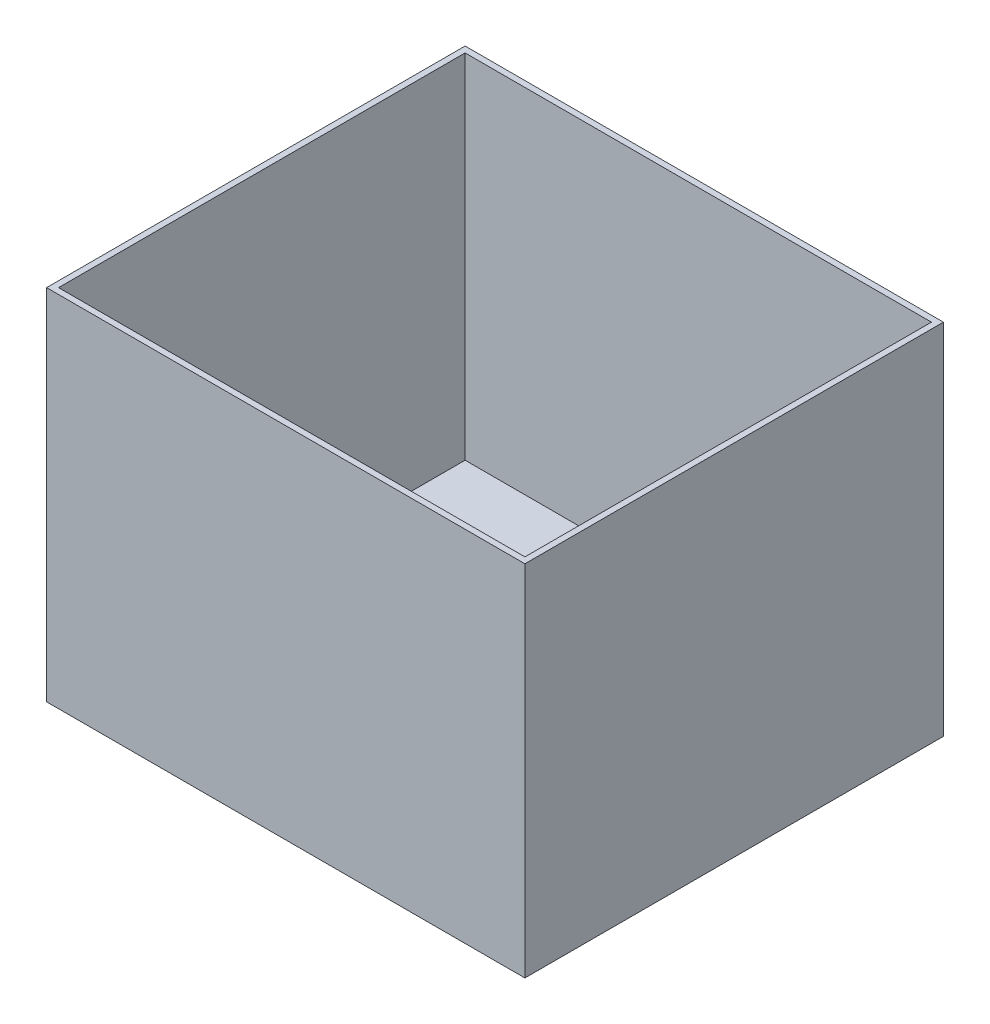
SolidWorks part; units mm, degrees
ref_plane "Front Plane" through (0, 0, 0) normal (0, 0, 1) x (1, 0, 0)
ref_plane "Top Plane" through (0, 0, 0) normal (0, 1, 0) x (1, 0, 0)
ref_plane "Right Plane" through (0, 0, 0) normal (1, 0, 0) x (0, 0, -1)
sketch "Sketch1" plane through (0, 0, 0) normal (0, 1, 0) x (1, 0, 0)
  line L1 (0, 0) -> (400, 0)
  line L2 (0, 0) -> (0, 350)
  line L3 (0, 350) -> (400, 350)
  line L4 (400, 0) -> (400, 350)
  dimension "D1" = 400
  dimension "D2" = 350
extrude "Boss-Extrude1" add sketch "Sketch1" along normal blind 300
shell "Shell1" thickness 5
